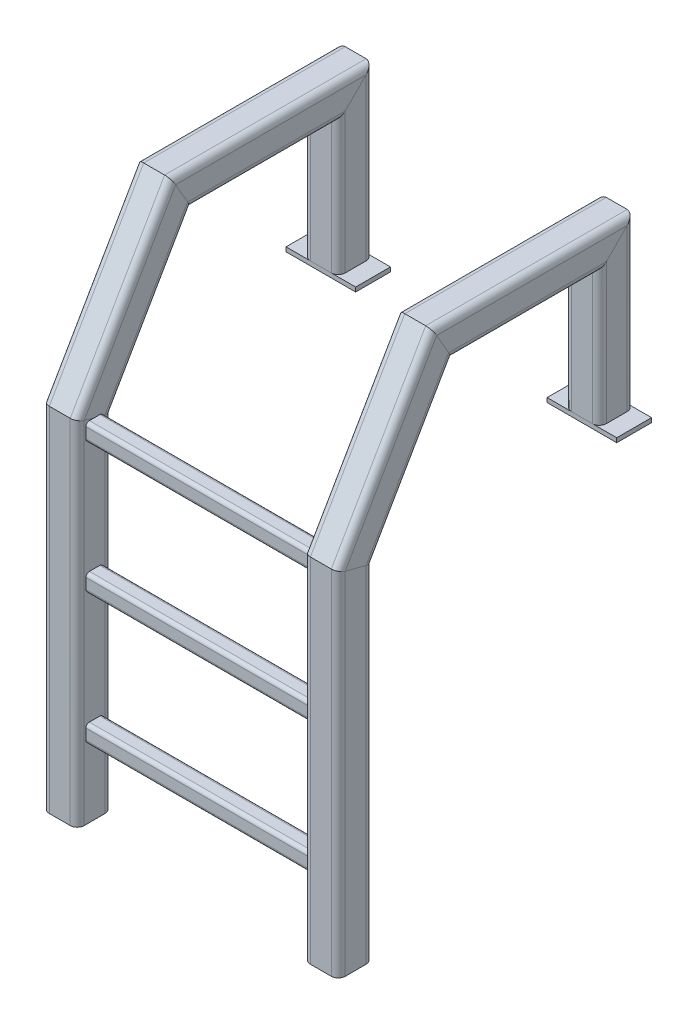
SolidWorks part; units mm, degrees
ref_plane "Front Plane" through (0, 0, 0) normal (0, 0, 1) x (1, 0, 0)
ref_plane "Top Plane" through (0, 0, 0) normal (0, 1, 0) x (1, 0, 0)
ref_plane "Right Plane" through (0, 0, 0) normal (1, 0, 0) x (0, 0, -1)
sketch "Sketch1" plane through (0, 0, 0) normal (1, 0, 0) x (0, 0, -1)
  line L0 (150, 0) -> (-150, 0) construction
  line L1 (150, 0) -> (150, 173.2051)
  line L2 (150, 173.2051) -> (-50, 173.2051)
  line L3 (-50, 173.2051) -> (-150, 0)
  line L4 (-150, 0) -> (-150, -400)
  point P3 (0, 0)
  dimension "D1" = 60
  dimension "D3" = 200
  dimension "D4" = 400
  dimension "D5" = 300
sketch3d "3DSketch1"
  line L0 (0, 173.2051, 50) -> (-300, 173.2051, 50)
  line L1 (0, 173.2051, -150) -> (-300, 173.2051, -150)
  line L2 (0, 0, 150) -> (-300, 0, 150)
  line L3 (0, 0, -150) -> (-300, 0, -150)
  line L4 (-300, -10, 150) -> (0, -10, 150)
  line L5 (-300, 0, -150) -> (-300, 173.2051, -150)
  line L6 (-300, 173.2051, 50) -> (-300, 173.2051, -150)
  line L7 (-300, 173.2051, 50) -> (-300, 0, 150)
  line L8 (-300, 0, 150) -> (-300, -400, 150)
  line L9 (0, 0, 150) -> (0, -400, 150) construction
  line L11 (-300, -160, 150) -> (0, -160, 150)
  line L12 (-300, -310, 150) -> (0, -310, 150)
  dimension "D1" = 150
  dimension "D2" = 150
  dimension "D3" = 160
other "Square tube 40 X 40 X 4(1)"
ref_plane "Plane1" through (0, 0, -150) normal (0, 1, 0) x (0, 0, 1)
sketch "Sketch13" plane through (0, 0, -150) normal (0, 1, 0) x (0, 0, 1)
  line L0 (-12, -16) -> (12, -16)
  line L1 (-16, -12) -> (-16, 12)
  line L2 (12, 16) -> (-12, 16)
  line L3 (16, 12) -> (16, -12)
  line L4 (-12, -20) -> (12, -20)
  line L5 (-20, -12) -> (-20, 12)
  line L6 (12, 20) -> (-12, 20)
  line L7 (20, 12) -> (20, -12)
  arc A0 (20, 12) -> (12, 20) centre (12, 12) ccw
  arc A1 (12, -20) -> (20, -12) centre (12, -12) ccw
  arc A2 (-20, -12) -> (-12, -20) centre (-12, -12) ccw
  arc A3 (-12, 20) -> (-20, 12) centre (-12, 12) ccw
  arc A4 (-12, 16) -> (-16, 12) centre (-12, 12) ccw
  arc A5 (16, 12) -> (12, 16) centre (12, 12) ccw
  arc A6 (12, -16) -> (16, -12) centre (12, -12) ccw
  arc A7 (-16, -12) -> (-12, -16) centre (-12, -12) ccw
  point P0 (-20, 0)
  point P1 (20, 0)
  point P2 (0, 20)
  point P3 (0, -20)
  point P4 (0, 0)
  point P5 (-20, -20)
  point P6 (20, -20)
  point P7 (20, 20)
  point P8 (-20, 20)
  point P33 (0, 0)
  point P35 (0, 0)
  point P36 (0, 0)
  point P37 (0, 0)
  point P38 (0, 0)
  point P39 (0, 0)
  point P40 (0, 0)
  dimension "D1" = 8
  dimension "Thickness" = 4
  dimension "V_leg" = 40
sketch "Sketch14" plane through (0, 0, 0) normal (0, -1, 0) x (1, 0, 0)
  line L1 (-340, -130) -> (-260, -130)
  line L2 (-340, -130) -> (-340, -170)
  line L3 (-340, -170) -> (-260, -170)
  line L4 (-260, -130) -> (-260, -170)
  line L5 (-340, -130) -> (-260, -170) construction
  line L6 (-340, -170) -> (-260, -130) construction
  line L7 (-40, -130) -> (40, -130)
  line L8 (-40, -130) -> (-40, -170)
  line L9 (-40, -170) -> (40, -170)
  line L10 (40, -130) -> (40, -170)
  line L11 (-40, -130) -> (40, -170) construction
  line L12 (-40, -170) -> (40, -130) construction
  point P0 (-300, -150)
  point P6 (0, -150)
  dimension "D1" = 80
  dimension "D2" = 80
  dimension "D3" = 40
  dimension "D4" = 40
extrude "Boss-Extrude1" add sketch "Sketch14" along normal blind 5 separate body
other "Square tube 20 X 20 X 2(1)"
ref_plane "Plane2" through (-300, -10, 150) normal (1, 0, 0) x (0, 0, -1)
sketch "Sketch15" plane through (-300, -10, 150) normal (1, 0, 0) x (0, 0, -1)
  line L0 (-6, -8) -> (6, -8)
  line L1 (-8, -6) -> (-8, 6)
  line L2 (6, 8) -> (-6, 8)
  line L3 (8, 6) -> (8, -6)
  line L4 (-6, -10) -> (6, -10)
  line L5 (-10, -6) -> (-10, 6)
  line L6 (6, 10) -> (-6, 10)
  line L7 (10, 6) -> (10, -6)
  arc A0 (10, 6) -> (6, 10) centre (6, 6) ccw
  arc A1 (6, -10) -> (10, -6) centre (6, -6) ccw
  arc A2 (-10, -6) -> (-6, -10) centre (-6, -6) ccw
  arc A3 (-6, 10) -> (-10, 6) centre (-6, 6) ccw
  arc A4 (-6, 8) -> (-8, 6) centre (-6, 6) ccw
  arc A5 (8, 6) -> (6, 8) centre (6, 6) ccw
  arc A6 (6, -8) -> (8, -6) centre (6, -6) ccw
  arc A7 (-8, -6) -> (-6, -8) centre (-6, -6) ccw
  point P0 (-10, 0)
  point P1 (10, 0)
  point P2 (0, 10)
  point P3 (0, -10)
  point P4 (0, 0)
  point P5 (-10, -10)
  point P6 (10, -10)
  point P7 (10, 10)
  point P8 (-10, 10)
  point P33 (0, 0)
  dimension "D1" = 4
  dimension "Thickness" = 2
  dimension "V_leg" = 20
